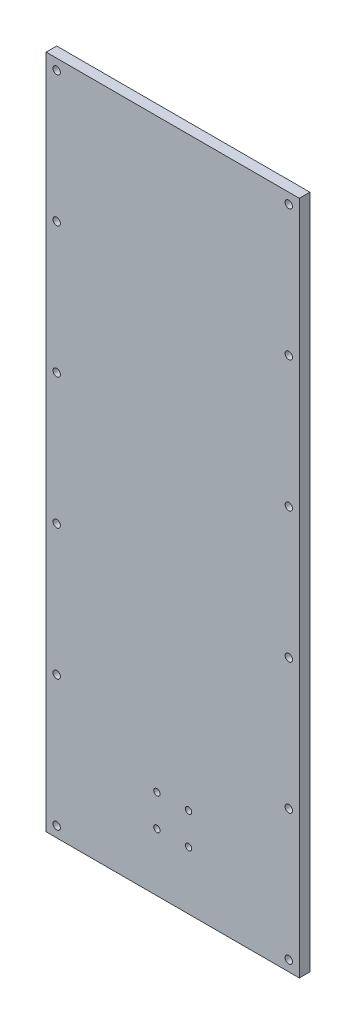
SolidWorks part; units mm, degrees
ref_plane "Plan de face" through (0, 0, 0) normal (0, 0, 1) x (1, 0, 0)
ref_plane "Plan de dessus" through (0, 0, 0) normal (0, 1, 0) x (1, 0, 0)
ref_plane "Plan de droite" through (0, 0, 0) normal (1, 0, 0) x (0, 0, -1)
sketch "Esquisse1" plane through (0, 0, 0) normal (0, 0, 1) x (1, 0, 0)
  line L1 (60, -160) -> (-60, -160)
  line L2 (60, -160) -> (60, 160)
  line L3 (60, 160) -> (-60, 160)
  line L4 (-60, -160) -> (-60, 160)
  line L5 (60, -160) -> (-60, 160) construction
  line L6 (60, 160) -> (-60, -160) construction
  point P0 (0, 0)
  dimension "D1" = 320
  dimension "D2" = 120
extrude "Boss.-Extru.1" add sketch "Esquisse1" along normal blind 5
sketch "Esquisse2" plane through (0, 0, 5) normal (0, 0, 1) x (1, 0, 0)
  line L0 (60, 160) -> (-60, 160) construction
  line L2 (-55, 155) -> (60, 155) construction
  line L3 (60, -160) -> (60, 160) construction
  line L4 (-55, 155) -> (-55, -160) construction
  line L5 (-60, -160) -> (60, -160) construction
  line L6 (-7.5, -117.5) -> (7.5, -117.5) construction
  line L7 (0, 0) -> (0, -160) construction
  line L8 (7.5, -137.5) -> (-7.5, -137.5) construction
  line L9 (12.5, -132.5) -> (12.5, -117.5) construction
  line L10 (7.5, -112.5) -> (-7.5, -112.5) construction
  line L11 (-12.5, -132.5) -> (-12.5, -117.5) construction
  line L12 (12.5, -137.5) -> (-12.5, -112.5) construction
  line L13 (12.5, -112.5) -> (-12.5, -137.5) construction
  line L14 (-7.5, -117.5) -> (-7.5, -132.5) construction
  line L15 (55, 155) -> (55, -160) construction
  circle A0 centre (-55, 155) radius 1.7476
  circle A2 centre (55, 155) radius 1.7476
  circle A3 centre (-55, 93) radius 1.7476
  circle A4 centre (-55, 31) radius 1.7476
  circle A5 centre (-55, -31) radius 1.7476
  circle A6 centre (-55, -93) radius 1.7476
  circle A7 centre (-55, -155) radius 1.7476
  circle A11 centre (55, 93) radius 1.7476
  circle A12 centre (55, 31) radius 1.7476
  circle A13 centre (55, -31) radius 1.7476
  circle A14 centre (55, -93) radius 1.7476
  circle A15 centre (0, -125) radius 4.5 construction
  arc A16 (7.5, -137.5) -> (12.5, -132.5) centre (7.5, -132.5) ccw construction
  arc A17 (-7.5, -137.5) -> (-12.5, -132.5) centre (-7.5, -132.5) cw construction
  arc A18 (12.5, -117.5) -> (7.5, -112.5) centre (7.5, -117.5) ccw construction
  arc A19 (-7.5, -112.5) -> (-12.5, -117.5) centre (-7.5, -117.5) ccw construction
  circle A20 centre (-7.5, -117.5) radius 1.5
  circle A21 centre (7.5, -117.5) radius 1.5
  circle A22 centre (7.5, -132.5) radius 1.5
  circle A23 centre (-7.5, -132.5) radius 1.5
  circle A24 centre (55, -155) radius 1.7476
  circle A25 centre (0, 155) radius 1.7476 [skipped]
  point P4 (0, 0)
  dimension "D8" = 9
  dimension "D10" = 5
  dimension "D12" = 3
  dimension "D1" = 5
  dimension "D4" = 5
  dimension "D6" = 5
  dimension "D9" = 35
  dimension "D11" = 25
  dimension "D3" = 3
  dimension "D5" = 6
  dimension "D13" = 2
  dimension "D14" = 2
extrude "Enlèv. mat.-Extru.1" cut sketch "Esquisse2" against normal blind 10
